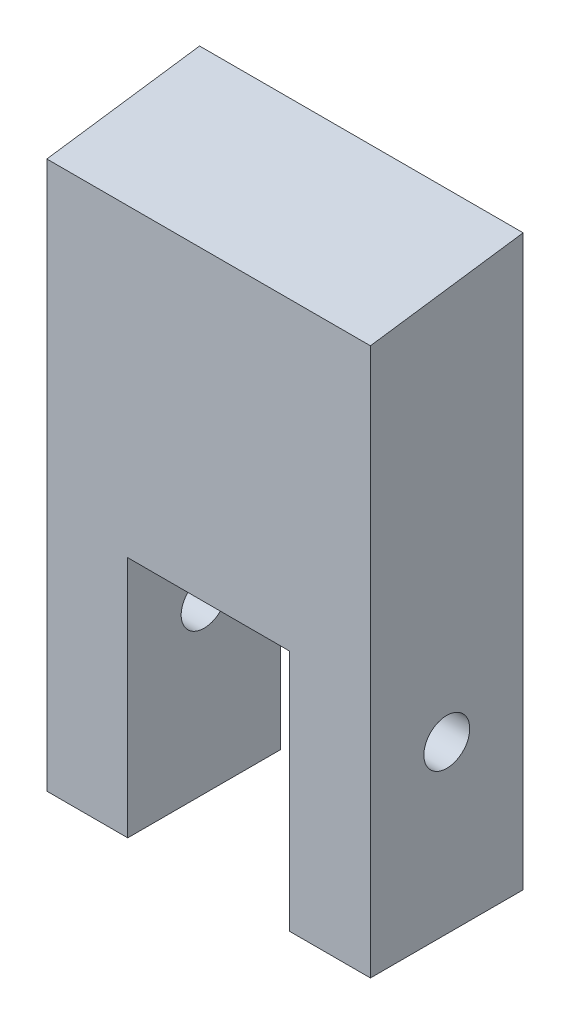
SolidWorks part; units mm, degrees
ref_plane "Front Plane" through (0, 0, 0) normal (0, 0, 1) x (1, 0, 0)
ref_plane "Top Plane" through (0, 0, 0) normal (0, 1, 0) x (1, 0, 0)
ref_plane "Right Plane" through (0, 0, 0) normal (1, 0, 0) x (0, 0, -1)
sketch "Sketch1" plane through (0, 0, 0) normal (1, 0, 0) x (0, 0, -1)
  line L0 (0, 0) -> (11.9888, 0)
  line L1 (11.9888, 0) -> (11.9888, 44.6631)
  line L2 (11.9888, 44.6631) -> (0, 42.9782)
  line L3 (0, 42.9782) -> (0, 0)
  line L4 (0, 15.5448) -> (11.9888, 15.5448) construction
  line L5 (0, 42.9782) -> (-195.199, 15.5448) construction
  line L6 (-195.199, 15.5448) -> (0, 15.5448) construction
  dimension "D1" = 8
  dimension "D2" = 11.9888
  dimension "D3" = 207.1878
  dimension "D4" = 15.5448
extrude "Boss-Extrude1" add sketch "Sketch1" along normal blind 25.4
sketch "Sketch2" plane through (0, 0, 0) normal (0, 0, 1) x (1, 0, 0)
  line L0 (25.4, 0) -> (0, 0) construction
  line L1 (6.35, 19.05) -> (19.05, 19.05)
  line L2 (6.35, 19.05) -> (6.35, 0)
  line L3 (6.35, 0) -> (19.05, 0)
  line L4 (19.05, 19.05) -> (19.05, 0)
  line L5 (6.35, 19.05) -> (19.05, 0) construction
  line L6 (6.35, 0) -> (19.05, 19.05) construction
  point P0 (12.7, 9.525)
  point P7 (12.7, 0)
  dimension "D1" = 19.05
  dimension "D2" = 12.7
extrude "Cut-Extrude1" cut sketch "Sketch2" against normal through all
hole_wizard "M3 Clearance Hole1" positions "Sketch3" profile "Sketch4" hole size "M3" standard "ANSI Metric" end condition through all
sketch "Sketch3" plane through (25.4, 0, 0) normal (1, 0, 0) x (0, 0, -1)
  line L0 (11.9888, 19.05) -> (0, 19.05) construction
  line L2 (11.9888, 0) -> (11.9888, 44.6631) construction
  point P0 (5.9944, 13.0556)
  dimension "D1" = 5.9944
  dimension "D2" = 5.9944
sketch "Sketch4" plane through (25.4, 13.0556, -5.9944) normal (0, 1, 0) x (0, 0, -1)
  line L0 (0, 0) -> (0, 25.4)
  line L1 (0, 25.4) -> (1.8, 25.4)
  line L2 (1.8, 25.4) -> (1.8, 0)
  line L5 (1.8, 0) -> (0, 0)
  line L11 (0, -6.35) -> (0, 107.95) construction
  dimension "Thru Hole Dia." = 3.6
  dimension "Thru Hole Depth" = 25.4
